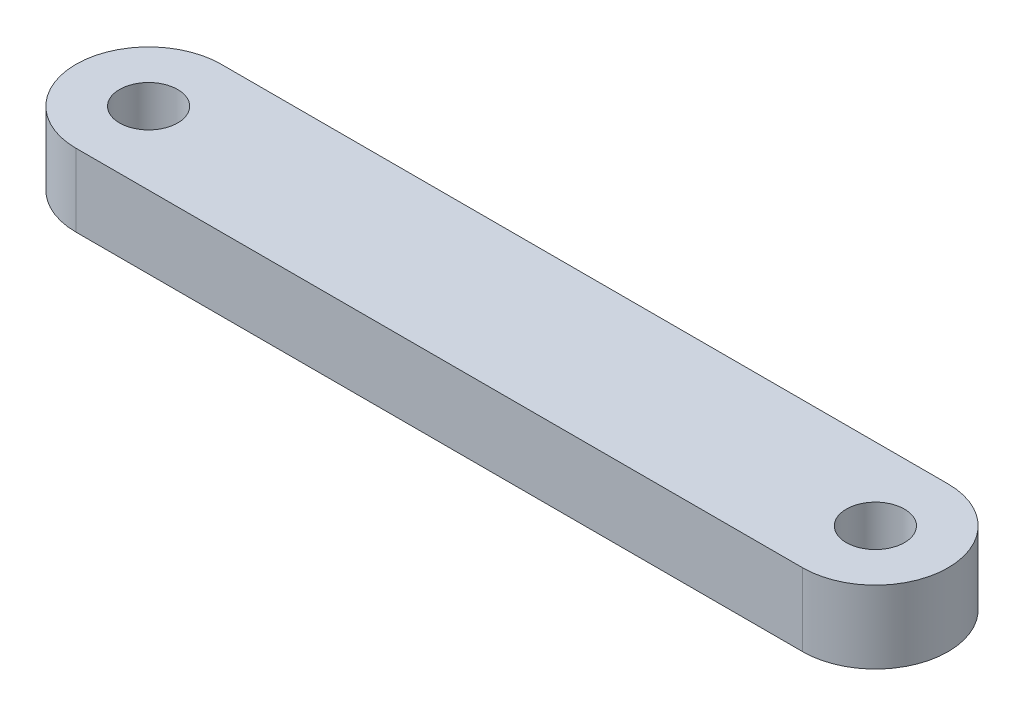
SolidWorks part; units mm, degrees
ref_plane "前视基准面" through (0, 0, 0) normal (0, 0, 1) x (1, 0, 0)
ref_plane "上视基准面" through (0, 0, 0) normal (0, 1, 0) x (1, 0, 0)
ref_plane "右视基准面" through (0, 0, 0) normal (1, 0, 0) x (0, 0, -1)
sketch "草图1" plane through (0, 0, 0) normal (0, 1, 0) x (1, 0, 0)
  line L0 (0, 0) -> (50, 0)
  line L2 (50, 10) -> (0, 10)
  arc A0 (0, 10) -> (0, 0) centre (0, 5) ccw
  arc A1 (50, 0) -> (50, 10) centre (50, 5) ccw
  dimension "D1" = 50
  dimension "D2" = 10
extrude "凸台-拉伸1" add sketch "草图1" along normal blind 5
sketch "草图2" plane through (0, 5, 0) normal (0, 1, 0) x (1, 0, 0)
  line L0 (0, 10) -> (0, 0) construction
  line L1 (50, 10) -> (50, 0) construction
  circle A0 centre (0, 5) radius 2
  circle A1 centre (50, 5) radius 2
extrude "切除-拉伸1" cut sketch "草图2" against normal blind 5
